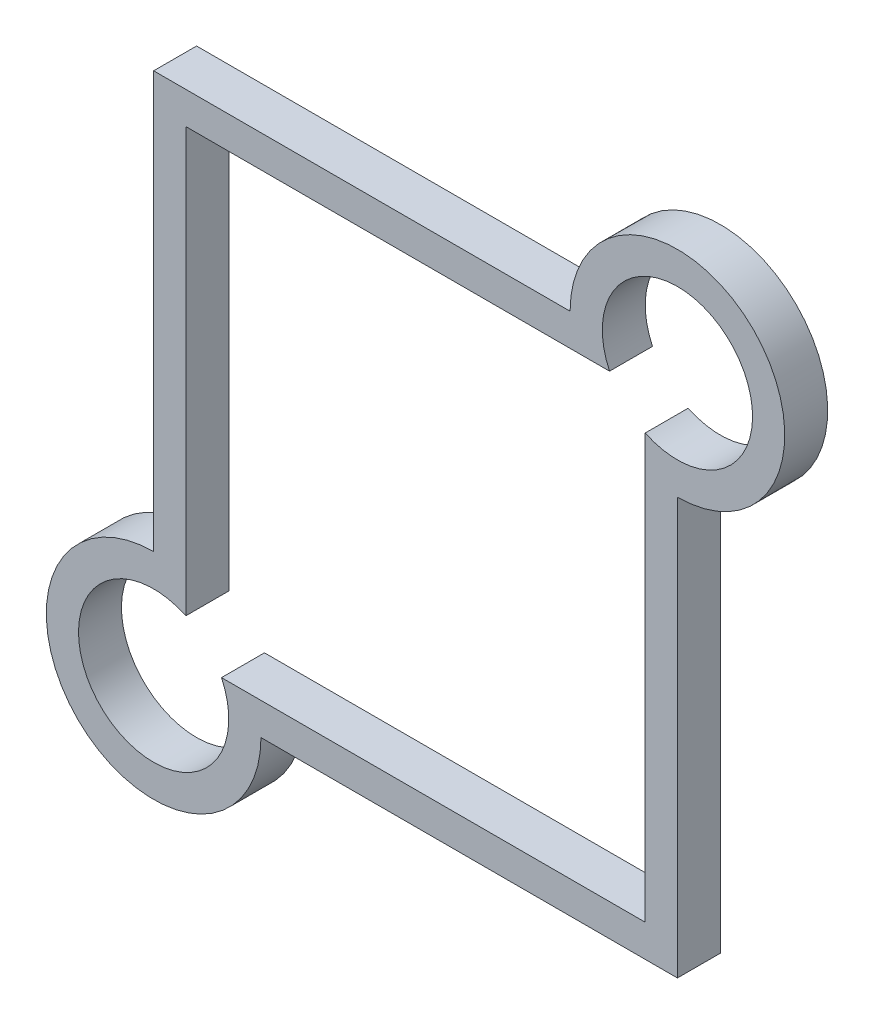
SolidWorks part; units mm, degrees
ref_plane "Front Plane" through (0, 0, 0) normal (0, 0, 1) x (1, 0, 0)
ref_plane "Top Plane" through (0, 0, 0) normal (0, 1, 0) x (1, 0, 0)
ref_plane "Right Plane" through (0, 0, 0) normal (1, 0, 0) x (0, 0, -1)
sketch "Sketch1" plane through (0, 0, 0) normal (0, 0, 1) x (1, 0, 0)
  line L0 (-122, 122) -> (72, 122)
  line L1 (-107, 107) -> (90.3772, 107)
  line L2 (-107, 107) -> (-107, -90.3772)
  line L3 (-90.3772, -107) -> (107, -107)
  line L4 (107, 90.3772) -> (107, -107)
  line L5 (-107, 107) -> (107, -107) construction
  line L6 (-107, -107) -> (107, 107) construction
  line L7 (122, 72) -> (122, -122)
  line L8 (-72, -122) -> (122, -122)
  line L9 (-122, 122) -> (-122, -72)
  line L11 (-122, 122) -> (122, 122) construction
  line L12 (122, 122) -> (122, -122) construction
  line L13 (-107, 107) -> (107, 107) construction
  line L14 (107, 107) -> (107, -107) construction
  line L15 (-122, -122) -> (122, -122) construction
  line L16 (-122, 122) -> (-122, -122) construction
  line L17 (-107, -107) -> (107, -107) construction
  line L18 (-107, 107) -> (-107, -107) construction
  arc A4 (107, 90.3772) -> (90.3772, 107) centre (122, 122) ccw
  arc A5 (-107, -90.3772) -> (-90.3772, -107) centre (-122, -122) ccw
  arc A6 (122, 72) -> (72, 122) centre (122, 122) ccw
  arc A7 (-122, -72) -> (-72, -122) centre (-122, -122) ccw
  circle A9 centre (122, 122) radius 50 construction
  circle A10 centre (122, 122) radius 35 construction
  circle A11 centre (-122, -122) radius 50 construction
  circle A12 centre (-122, -122) radius 35 construction
  point P0 (0, 0)
  point P13 (155.4707, 132.233)
  point P16 (172, 122)
  point P24 (-72, -122)
  point P29 (-88.5293, -111.767)
  dimension "D3" = 70
  dimension "D5" = 70
  dimension "D1" = 214
  dimension "D2" = 214
  dimension "D4" = 15
  dimension "D6" = 15
  dimension "D7" = 15
extrude "Boss-Extrude1" add sketch "Sketch1" along normal blind 20
